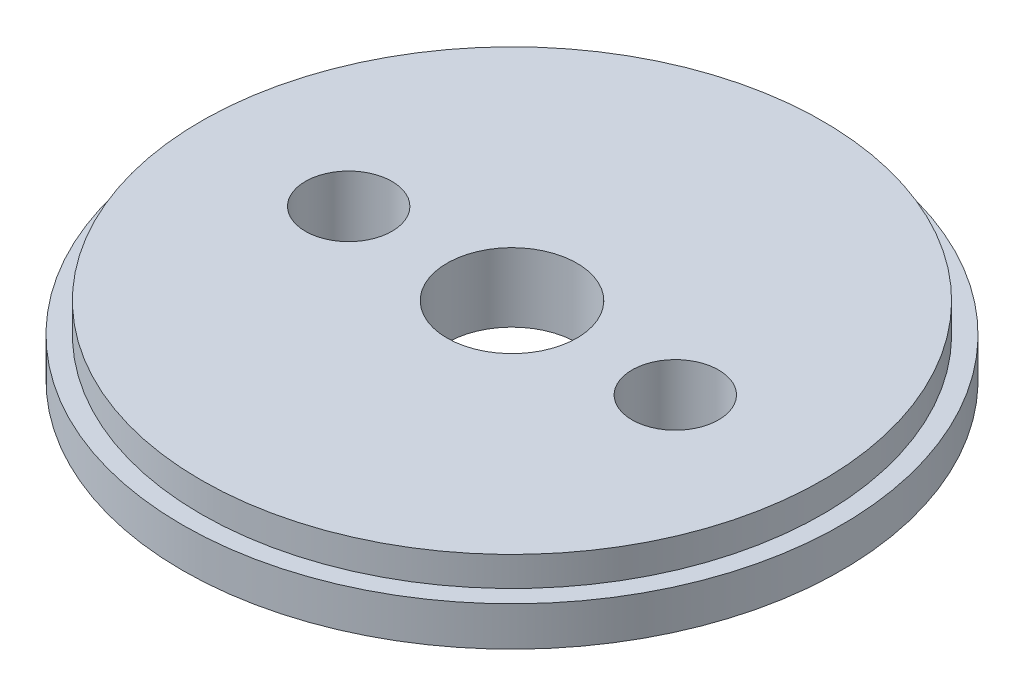
SolidWorks part; units mm, degrees
ref_plane "Front Plane" through (0, 0, 0) normal (0, 0, 1) x (1, 0, 0)
ref_plane "Top Plane" through (0, 0, 0) normal (0, 1, 0) x (1, 0, 0)
ref_plane "Right Plane" through (0, 0, 0) normal (1, 0, 0) x (0, 0, -1)
sketch "Sketch1" plane through (0, 0, 0) normal (0, 1, 0) x (1, 0, 0)
  circle A0 centre (0, 0) radius 16.75
  dimension "D1" = 33.5
extrude "Boss-Extrude1" add sketch "Sketch1" along normal blind 3.5
sketch "Sketch2" plane through (0, 3.5, 0) normal (0, 1, 0) x (1, 0, 0)
  circle A0 centre (0, 0) radius 15.8
  dimension "D1" = 31.6
extrude "Cut-Extrude1" cut sketch "Sketch2" against normal blind 1.5 flip side to cut
sketch "Sketch3" plane through (0, 3.5, 0) normal (0, 1, 0) x (1, 0, 0)
  line L0 (-22.4911, 0) -> (26.1714, 0) construction
  line L1 (0, 22.3766) -> (0, -23.9749) construction
  line L2 (-16.75, 0) -> (-8.3, 0)
  circle A0 centre (0, 0) radius 3.3
  circle A1 centre (0, 0) radius 16.75 construction
  circle A2 centre (-8.3, 0) radius 2.2
  circle A3 centre (8.3, 0) radius 2.2
  circle A4 centre (0, 0) radius 15.8 construction
  circle A5 centre (0, 0) radius 15.8
  point P14 (-15.8, 0)
  dimension "D1" = 8.3
  dimension "D3" = 4.4
  dimension "D4" = 6.6
  dimension "D5" = 31.6
  dimension "D2" = 7.5
extrude "Cut-Extrude2" cut sketch "Sketch3" against normal through all
